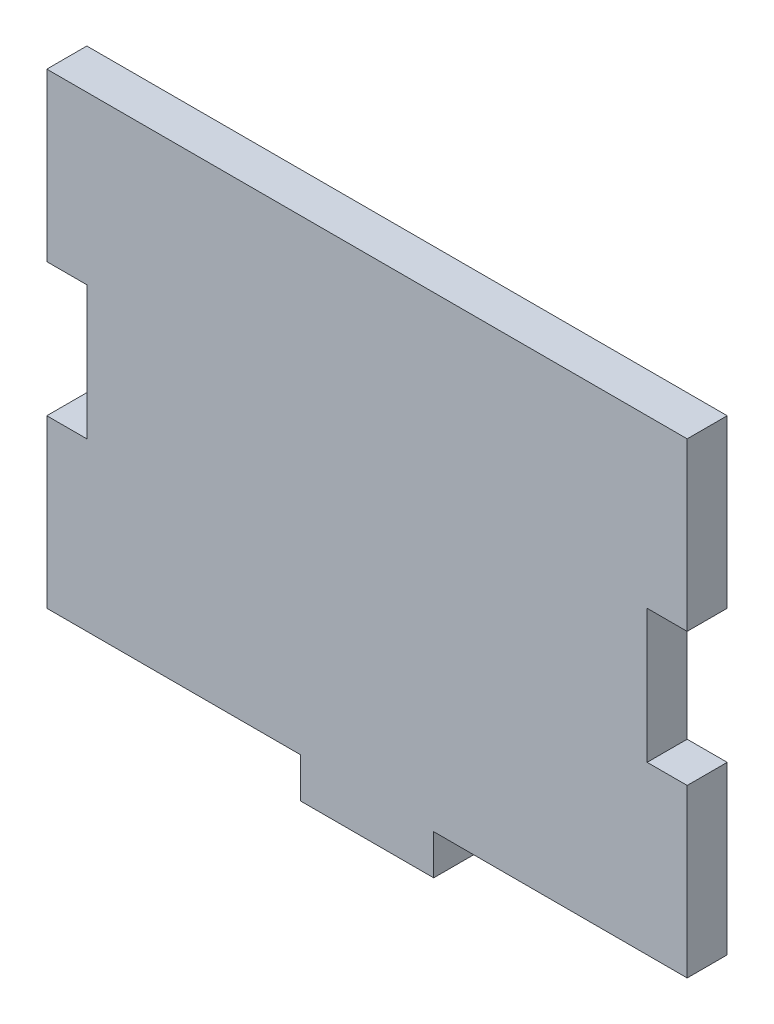
SolidWorks part; units mm, degrees
ref_plane "Front Plane" through (0, 0, 0) normal (0, 0, 1) x (1, 0, 0)
ref_plane "Top Plane" through (0, 0, 0) normal (0, 1, 0) x (1, 0, 0)
ref_plane "Right Plane" through (0, 0, 0) normal (1, 0, 0) x (0, 0, -1)
sketch "Sketch1" plane through (0, 0, 0) normal (0, 0, 1) x (1, 0, 0)
  line L0 (-5, -17.5) -> (-5, -20.5)
  line L1 (24, -17.5) -> (5, -17.5)
  line L2 (24, -17.5) -> (24, -5)
  line L3 (24, 17.5) -> (-24, 17.5)
  line L4 (-24, -17.5) -> (-24, -5)
  line L5 (24, -17.5) -> (-24, 17.5) construction
  line L6 (24, 17.5) -> (-24, -17.5) construction
  line L7 (-5, -20.5) -> (5, -20.5)
  line L8 (5, -20.5) -> (5, -17.5)
  line L9 (-24, -5) -> (-21, -5)
  line L10 (-21, -5) -> (-21, 5)
  line L11 (-21, 5) -> (-24, 5)
  line L12 (0, 0) -> (0, 17.5) construction
  line L13 (24, -5) -> (21, -5)
  line L14 (21, -5) -> (21, 5)
  line L15 (21, 5) -> (24, 5)
  line L16 (-24, 5) -> (-24, 17.5)
  line L17 (24, 5) -> (24, 17.5)
  line L18 (-5, -17.5) -> (-24, -17.5)
  point P0 (0, 0)
  dimension "D1" = 48
  dimension "D2" = 35
  dimension "D3" = 10
  dimension "D4" = 3
  dimension "D5" = 19
  dimension "D6" = 3
  dimension "D7" = 10
  dimension "D8" = 12.5
extrude "Boss-Extrude1" add sketch "Sketch1" along normal blind 3
